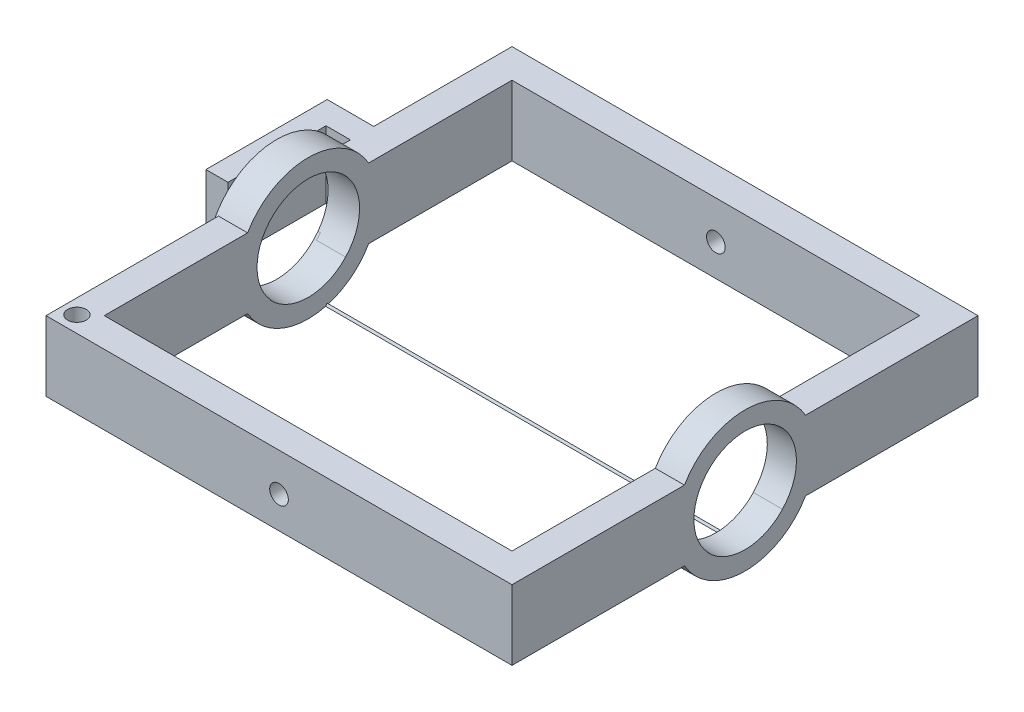
SolidWorks part; units mm, degrees
ref_plane "Front Plane" through (0, 0, 0) normal (0, 0, 1) x (1, 0, 0)
ref_plane "Top Plane" through (0, 0, 0) normal (0, 1, 0) x (1, 0, 0)
ref_plane "Right Plane" through (0, 0, 0) normal (1, 0, 0) x (0, 0, -1)
sketch "Sketch1" plane through (0, 0, 0) normal (0, 1, 0) x (1, 0, 0)
  line L1 (-100, 100) -> (100, 100)
  line L2 (-100, 100) -> (-100, -100)
  line L3 (-100, -100) -> (100, -100)
  line L4 (100, 100) -> (100, -100)
  line L5 (-100, 100) -> (100, -100) construction
  line L6 (-100, -100) -> (100, 100) construction
  point P0 (0, 0)
extrude "Boss-Extrude1" add sketch "Sketch1" along normal blind 30
sketch "Sketch4" plane through (0, 30, 0) normal (0, 1, 0) x (1, 0, 0)
  line L1 (-87.5, -87.5) -> (87.5, -87.5)
  line L2 (-87.5, -87.5) -> (-87.5, 87.5)
  line L3 (-87.5, 87.5) -> (87.5, 87.5)
  line L4 (87.5, -87.5) -> (87.5, 87.5)
  line L5 (-87.5, -87.5) -> (87.5, 87.5) construction
  line L6 (-87.5, 87.5) -> (87.5, -87.5) construction
  point P0 (0, 0)
extrude "Cut-Extrude1" cut sketch "Sketch4" against normal blind 30
sketch "Sketch7" plane through (-100, 0, 0) normal (-1, 0, 0) x (0, 0, 1)
  circle A0 centre (0, 15) radius 4
extrude "Cut-Extrude2" cut sketch "Sketch7" against normal blind 210
sketch "Sketch10" plane through (-100, 0, 0) normal (-1, 0, 0) x (0, 0, 1)
  line L0 (-8.6266, 30) -> (-8.6266, 0)
  line L1 (-100, 30) -> (100, 30) construction
  line L2 (-100, 0) -> (100, 0) construction
  line L3 (-8.6266, 0) -> (-14.6668, 0)
  line L4 (-14.6668, 0) -> (-14.6668, 30)
  line L5 (-14.6668, 30) -> (-8.6266, 30)
extrude "Boss-Extrude2" add sketch "Sketch10" along normal blind 20
sketch "Sketch11" plane through (0, 0, -8.6266) normal (0, 0, 1) x (1, 0, 0)
  line L0 (-120, 0) -> (-120, 30)
  line L1 (-120, 30) -> (-110, 30)
  line L2 (-120, 30) -> (-100, 30) construction
  line L3 (-110, 30) -> (-110, 0)
  line L4 (-120, 0) -> (-100, 0) construction
  line L5 (-110, 0) -> (-120, 0)
extrude "Boss-Extrude3" add sketch "Sketch11" along normal blind 20
sketch "Sketch12" plane through (100, 0, 0) normal (1, 0, 0) x (0, 0, -1)
  circle A0 centre (0, 15) radius 4
extrude "Cut-Extrude3" cut sketch "Sketch12" against normal blind 231
sketch "Sketch13" plane through (0, 30, 0) normal (0, 1, 0) x (1, 0, 0)
  circle A0 centre (-93.6945, -93.0455) radius 4
extrude "Cut-Extrude5" cut sketch "Sketch13" against normal blind 231
sketch "Sketch14" plane through (0, 0, 100) normal (0, 0, 1) x (1, 0, 0)
  circle A0 centre (0, 13.6147) radius 4
extrude "Cut-Extrude6" cut sketch "Sketch14" against normal blind 250.5
sketch "Sketch15" plane through (100, 0, 0) normal (1, 0, 0) x (0, 0, -1)
  circle A0 centre (0, 15) radius 30
  circle A1 centre (0, 15) radius 22
extrude "Boss-Extrude5" add sketch "Sketch15" against normal blind 201
sketch "Sketch17" plane through (100, 0, 0) normal (1, 0, 0) x (0, 0, -1)
  circle A0 centre (0.0744, 15.1008) radius 22
extrude "Cut-Extrude7" cut sketch "Sketch17" against normal blind 201
sketch "Sketch18" plane through (87.5, 0, 0) normal (-1, 0, 0) x (0, 0, 1)
  line L1 (-87.5, 0) -> (87.5, 0)
  line L2 (-87.5, 0) -> (-87.5, 30)
  line L3 (-87.5, 30) -> (87.5, 30)
  line L4 (87.5, 0) -> (87.5, 30)
sketch "Sketch21" plane through (0, 0, -14.6668) normal (0, 0, -1) x (-1, 0, 0)
  line L0 (120, 30) -> (120, 0) construction
  line L1 (120, 1.1441) -> (110.5, 1.1441)
  line L2 (120, 1.1441) -> (120, 30)
  line L3 (120, 30) -> (110.5, 30)
  line L4 (110.5, 1.1441) -> (110.5, 30)
  line L5 (120, 30) -> (101, 30) construction
extrude "Boss-Extrude6" add sketch "Sketch21" along normal blind 26
sketch "Sketch22" plane through (0, 30, 0) normal (0, 1, 0) x (1, 0, 0)
  line L1 (-110.5, 14.6668) -> (-101, 14.6668)
  line L2 (-110.5, 14.6668) -> (-110.5, 8.6266)
  line L3 (-110.5, 8.6266) -> (-101, 8.6266)
  line L4 (-101, 14.6668) -> (-101, 8.6266)
extrude "Cut-Extrude10" cut sketch "Sketch22" against normal blind 49
sketch "Sketch23" plane through (-110.5, 0, 0) normal (1, 0, 0) x (0, 0, -1)
  line L0 (40.6668, 1.1441) -> (14.6668, 1.1441) construction
  line L1 (40.6668, 30) -> (30.6579, 30)
  line L2 (40.6668, 30) -> (40.6668, 1.1441)
  line L3 (40.6668, 1.1441) -> (30.6579, 1.1441)
  line L4 (30.6579, 30) -> (30.6579, 1.1441)
extrude "Boss-Extrude7" add sketch "Sketch23" along normal blind 21
sketch "Sketch24" plane through (0, 0, -14.6668) normal (0, 0, -1) x (-1, 0, 0)
  line L1 (120, 0) -> (110.5, 0)
  line L2 (120, 0) -> (120, 1.1441)
  line L3 (120, 1.1441) -> (110.5, 1.1441)
  line L4 (110.5, 0) -> (110.5, 1.1441)
extrude "Cut-Extrude11" cut sketch "Sketch24" against normal blind 27
sketch "Sketch26" plane through (0, 0, 0) normal (0, -1, 0) x (1, 0, 0)
  line L1 (-110.5, -8.6266) -> (-109.9986, -8.6266)
  line L2 (-110.5, -8.6266) -> (-110.5, 12.267)
  line L3 (-110.5, 12.267) -> (-109.9986, 12.267)
  line L4 (-109.9986, -8.6266) -> (-109.9986, 12.267)
extrude "Cut-Extrude12" cut sketch "Sketch26" against normal blind 35
sketch "Sketch27" plane through (-87.5, 0, 0) normal (1, 0, 0) x (0, 0, -1)
  circle A0 centre (-31.9164, 15.3761) radius 49.1928
extrude "Cut-Extrude13" cut sketch "Sketch27" along normal blind 175
sketch "Sketch28" plane through (-87.5, 0, 0) normal (1, 0, 0) x (0, 0, -1)
  circle A0 centre (37.7624, 15.4944) radius 41.209
extrude "Cut-Extrude14" cut sketch "Sketch28" along normal blind 175
sketch "Sketch29" plane through (100, 0, 0) normal (1, 0, 0) x (0, 0, -1)
  circle A0 centre (0, 15) radius 30
